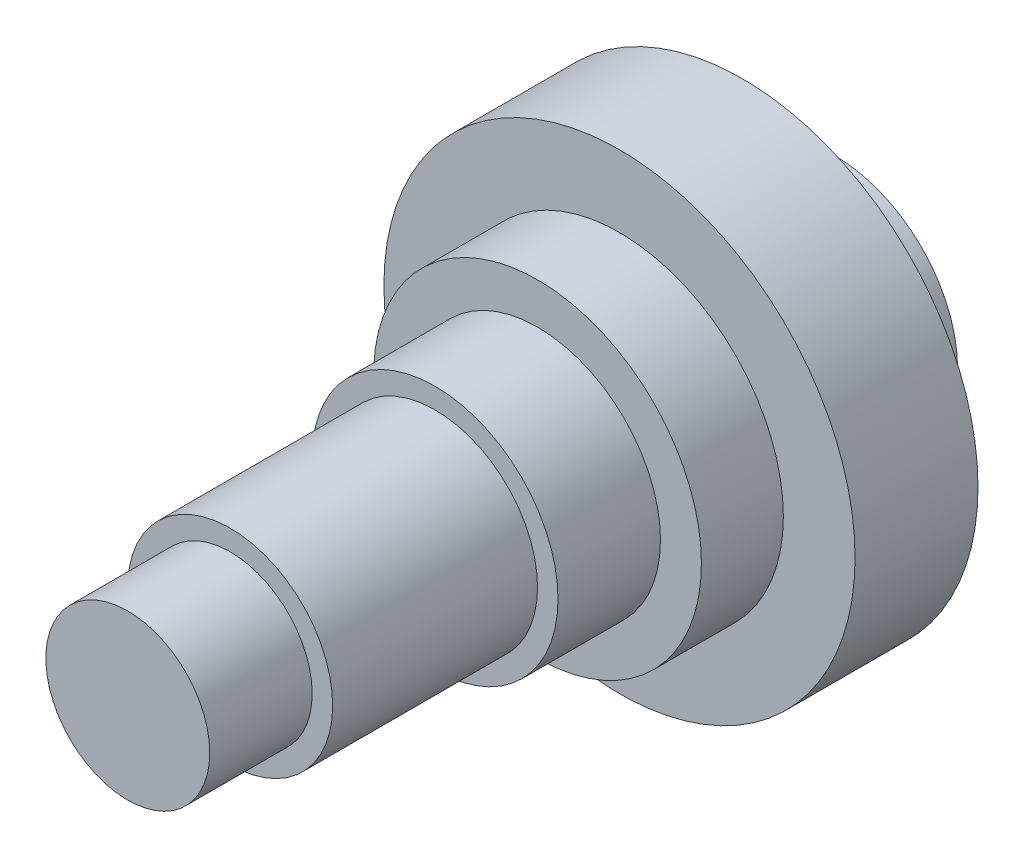
SolidWorks part; units mm, degrees
ref_plane "Front Plane" through (0, 0, 0) normal (0, 0, 1) x (1, 0, 0)
ref_plane "Top Plane" through (0, 0, 0) normal (0, 1, 0) x (1, 0, 0)
ref_plane "Right Plane" through (0, 0, 0) normal (1, 0, 0) x (0, 0, -1)
sketch "Sketch1" plane through (0, 0, 0) normal (1, 0, 0) x (0, 0, -1)
  line L0 (14.3002, 19.05) -> (0, 19.05)
  line L1 (0, 19.05) -> (0, 36.5125)
  line L2 (0, 36.5125) -> (-19.05, 36.5125)
  line L3 (-19.05, 36.5125) -> (-19.05, 25.4)
  line L4 (-19.05, 25.4) -> (-31.75, 25.4)
  line L5 (-31.75, 25.4) -> (-31.75, 19.05)
  line L6 (-31.75, 19.05) -> (-47.625, 19.05)
  line L7 (-47.625, 19.05) -> (-47.625, 15.875)
  line L8 (-47.625, 15.875) -> (-79.375, 15.875)
  line L9 (-79.375, 15.875) -> (-79.375, 12.7)
  line L10 (-79.375, 12.7) -> (-95.25, 12.7)
  line L11 (-95.25, 12.7) -> (-95.25, 0)
  line L12 (-95.25, 0) -> (14.3002, 0)
  line L13 (14.3002, 0) -> (14.3002, 19.05)
  line L14 (14.3002, 0) -> (63.0362, 0) construction
  dimension "D1" = 38.1
  dimension "D2" = 14.3002
  dimension "D3" = 19.05
  dimension "D4" = 12.7
  dimension "D5" = 15.875
  dimension "D6" = 63.5
  dimension "D7" = 15.875
  dimension "D8" = 25.4
  dimension "D9" = 31.75
  dimension "D10" = 38.1
  dimension "D11" = 50.8
  dimension "D12" = 73.025
revolve "Revolve1" add sketch "Sketch1" angle 360 about L14
